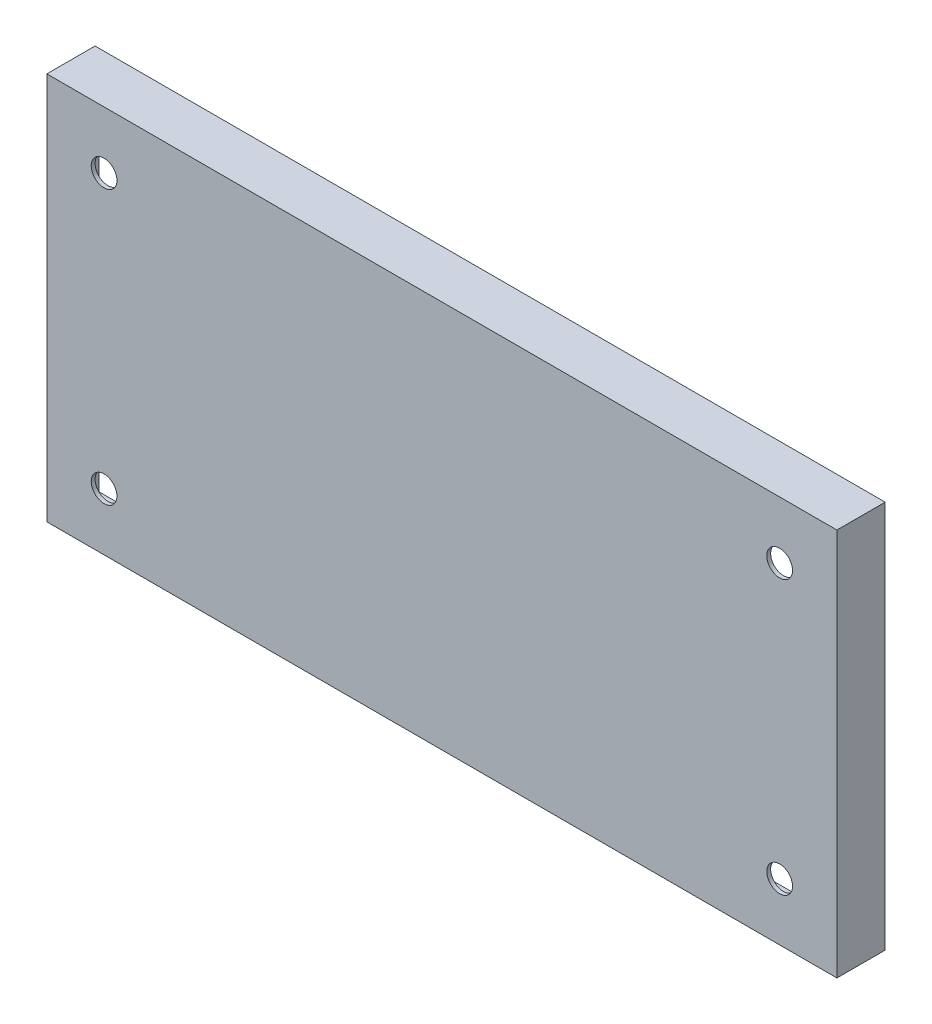
SolidWorks part; units mm, degrees
ref_plane "前视基准面" through (0, 0, 0) normal (0, 0, 1) x (1, 0, 0)
ref_plane "上视基准面" through (0, 0, 0) normal (0, 1, 0) x (1, 0, 0)
ref_plane "右视基准面" through (0, 0, 0) normal (1, 0, 0) x (0, 0, -1)
sketch "草图1" plane through (0, 0, 0) normal (0, 0, 1) x (1, 0, 0)
  line L0 (-122.8, -60.3) -> (-122.8, 60.3)
  line L1 (-122.8, -60.3) -> (122.8, -60.3)
  line L2 (-122.8, 60.3) -> (122.8, 60.3)
  line L3 (122.8, -60.3) -> (122.8, 60.3)
  line L4 (-122.8, -60.3) -> (122.8, 60.3) construction
  line L5 (-122.8, 60.3) -> (122.8, -60.3) construction
  point P1 (0, 0)
  dimension "D1" = 245.6
  dimension "D2" = 120.6
extrude "凸台-拉伸1" add sketch "草图1" along normal blind 15
shell "抽壳1" thickness 1.2
sketch "草图2" plane through (0, 0, 15) normal (0, 0, 1) x (1, 0, 0)
  line L8 (0, 0) -> (64.7146, 0) construction
  line L9 (0, 0) -> (0, 31.2342) construction
  circle A0 centre (-105, 42.5) radius 4
  circle A1 centre (105, 42.5) radius 4
  circle A2 centre (105, -42.5) radius 4
  circle A3 centre (-105, -42.5) radius 4
  dimension "D3" = 8
extrude "切除-拉伸1" cut sketch "草图2" against normal blind 15
